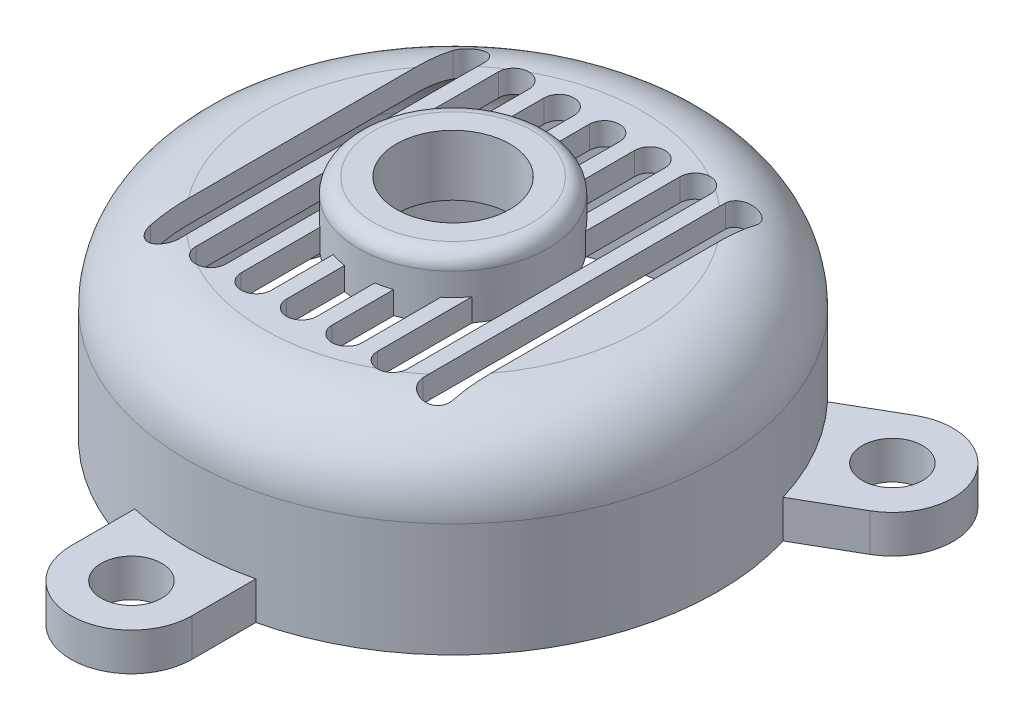
SolidWorks part; units mm, degrees
ref_plane "Front Plane" through (0, 0, 0) normal (0, 0, 1) x (1, 0, 0)
ref_plane "Top Plane" through (0, 0, 0) normal (0, 1, 0) x (1, 0, 0)
ref_plane "Right Plane" through (0, 0, 0) normal (1, 0, 0) x (0, 0, -1)
sketch "Sketch1" plane through (0, 0, 0) normal (0, 1, 0) x (1, 0, 0)
  circle A0 centre (0, 0) radius 35
  dimension "D1" = 70
extrude "Boss-Extrude1" add sketch "Sketch1" along normal blind 25
fillet "Fillet1" radius 10 1 edges at (0, 25, 35)
shell "Shell1" thickness 3
sketch "Sketch2" plane through (0, 0, 0) normal (0, -1, 0) x (1, 0, 0)
  line L2 (-8, 42.5) -> (-8, 32)
  line L3 (-8, 32) -> (8, 32)
  line L4 (8, 42.5) -> (8, 32)
  arc A0 (8, 42.5) -> (-8, 42.5) centre (0, 42.5) ccw
  circle A1 centre (0, 42.5) radius 4
  circle A3 centre (0, 0) radius 32 construction
  point P0 (-3.3806, 42.0367)
  point P7 (0, 0)
  point P9 (0, 0)
  dimension "D1" = 8
  dimension "D2" = 8
  dimension "D3" = 42.5
extrude "Boss-Extrude2" add sketch "Sketch2" against normal blind 5
pattern_circular "CirPattern1" count 3 over 360 about axis through (0, 0, 0) along (0, 1, 0) of "Boss-Extrude2"
sketch "Sketch3" plane through (0, 22, 0) normal (0, -1, 0) x (1, 0, 0)
  line L0 (-18, -20) -> (-18, 20) construction
  line L1 (-20, -20) -> (-20, 20)
  line L2 (-16, -20) -> (-16, 20)
  arc A0 (-20, -20) -> (-16, -20) centre (-18, -20) ccw
  arc A1 (-16, 20) -> (-20, 20) centre (-18, 20) ccw
  point P2 (-18, 0)
  point P7 (0, 0)
  dimension "D1" = 2
  dimension "D2" = 40
  dimension "D3" = 18
extrude "Cut-Extrude6" cut sketch "Sketch3" against normal mid plane 1000
sketch "Sketch7" plane through (0, 25, 0) normal (0, 1, 0) x (1, 0, 0)
  line L0 (0, 0) -> (17.533, 0)
pattern_linear "LPattern1" count 7 spacing 6 along (1, 0, 0) of "Cut-Extrude6"
sketch "Sketch8" plane through (0, 25, 0) normal (0, 1, 0) x (1, 0, 0)
  circle A0 centre (0, 0) radius 12.5
  dimension "D1" = 25
extrude "Boss-Extrude4" add sketch "Sketch8" along normal blind 5 and the other way blind 3
fillet "Fillet2" radius 2 1 edges at (0, 30, 12.5)
sketch "Sketch9" plane through (0, 30, 0) normal (0, 1, 0) x (1, 0, 0)
  circle A0 centre (0, 0) radius 7.5
  dimension "D1" = 15
extrude "Cut-Extrude7" cut sketch "Sketch9" against normal through all
